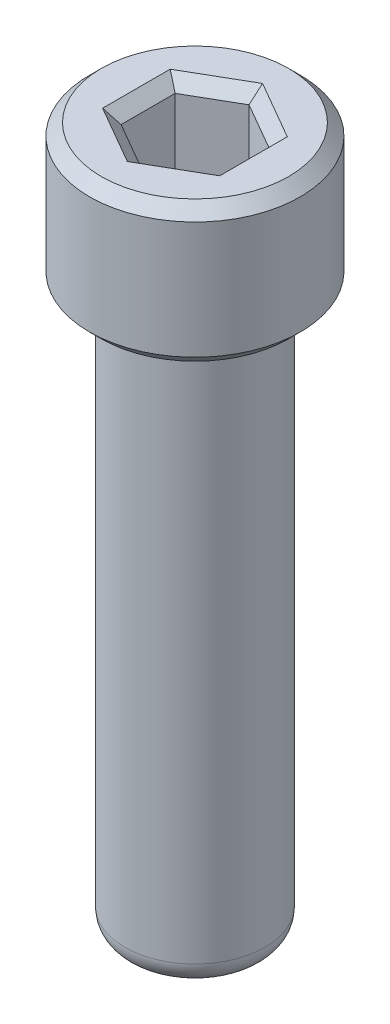
SolidWorks part; units mm, degrees
ref_plane "Front Plane" through (0, 0, 0) normal (0, 0, 1) x (1, 0, 0)
ref_plane "Top Plane" through (0, 0, 0) normal (0, 1, 0) x (1, 0, 0)
ref_plane "Right Plane" through (0, 0, 0) normal (1, 0, 0) x (0, 0, -1)
sketch "Sketch1" plane through (0, 0, 0) normal (0, 1, 0) x (1, 0, 0)
  circle A0 centre (0, 0) radius 1.5
  dimension "D1" = 3
extrude "Boss-Extrude1" add sketch "Sketch1" along normal blind 12
sketch "Sketch2" plane through (0, 12, 0) normal (0, 1, 0) x (1, 0, 0)
  circle A0 centre (0, 0) radius 2.25
  dimension "D1" = 4.5
extrude "Boss-Extrude2" add sketch "Sketch2" along normal blind 3
sketch "Sketch3" plane through (0, 15, 0) normal (0, 1, 0) x (1, 0, 0)
  line L1 (0, 1.1547) -> (-1, 0.5774)
  line L2 (-1, 0.5774) -> (-1, -0.5774)
  line L3 (-1, -0.5774) -> (0, -1.1547)
  line L4 (0, -1.1547) -> (1, -0.5774)
  line L5 (1, -0.5774) -> (1, 0.5774)
  line L6 (1, 0.5774) -> (0, 1.1547)
  circle A0 centre (0, 0) radius 1 construction
extrude "Cut-Extrude1" cut sketch "Sketch3" against normal blind 2
chamfer "Chamfer1" distance 0.25 angle 45 8 edges at (0, 12, 2.25) (0, 15, 2.25) (-0.5, 15, 0.866) (-1, 15, 0) (-0.5, 15, -0.866) (0.5, 15, -0.866) (1, 15, 0) (0.5, 15, 0.866)
fillet "Fillet1" radius 0.5 1 edges at (0, 0, 1.5)
